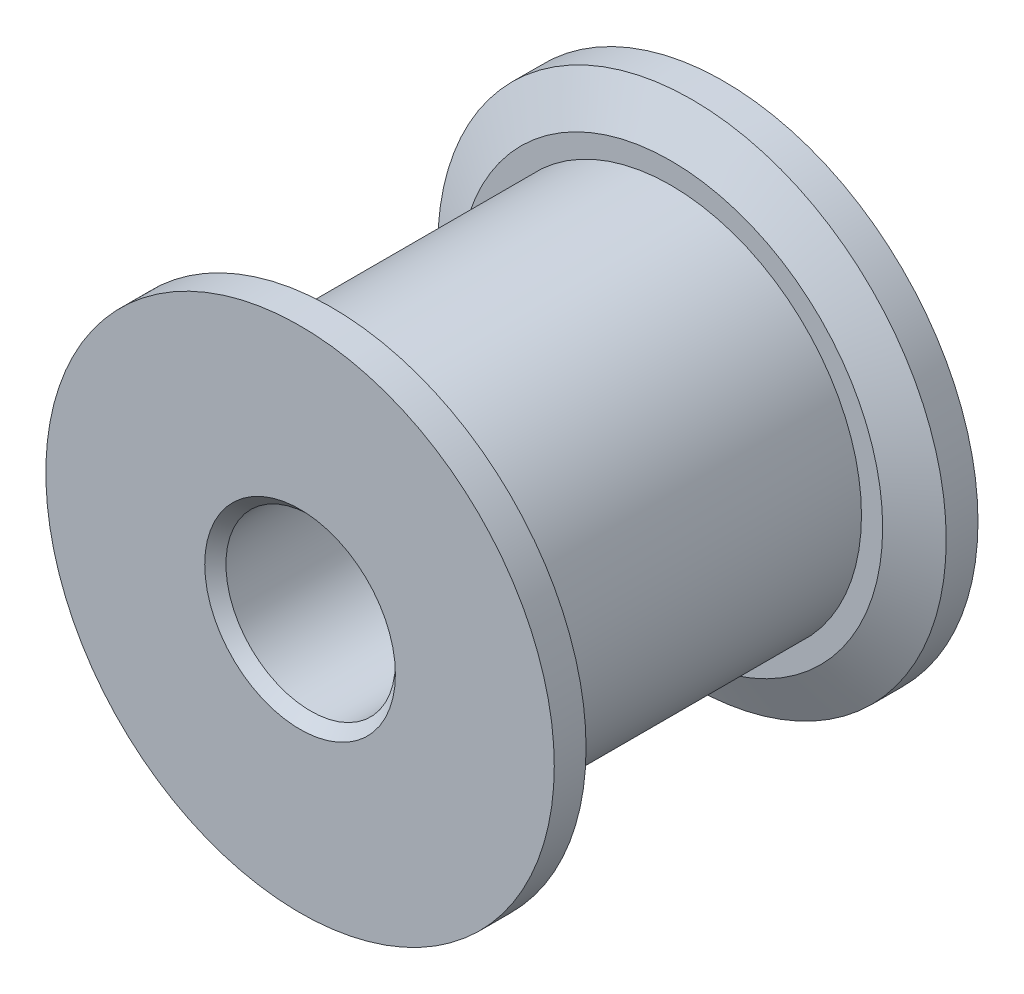
SolidWorks part; units mm, degrees
ref_plane "前视基准面" through (0, 0, 0) normal (0, 0, 1) x (1, 0, 0)
ref_plane "上视基准面" through (0, 0, 0) normal (0, 1, 0) x (1, 0, 0)
ref_plane "右视基准面" through (0, 0, 0) normal (1, 0, 0) x (0, 0, -1)
sketch "Sketch1" plane through (0, 0, 0) normal (0, 0, 1) x (1, 0, 0)
  circle A0 centre (0, 0) radius 18
  dimension "D1" = 36
extrude "Extrude1" add sketch "Sketch1" along normal mid plane 30
sketch "Sketch2" plane through (0, 0, 15) normal (0, 0, 1) x (1, 0, 0)
  circle A0 centre (0, 0) radius 24
  dimension "D1" = 48
extrude "Extrude2" add sketch "Sketch2" along normal blind 5
chamfer "Chamfer2" distance 4 distance2 2 1 edges at (24, 0, 15)
mirror "Mirror2" about plane through (0, 0, 0) normal (0, 0, 1) of "Chamfer2", "Extrude2"
sketch "Sketch3" plane through (0, 0, 0) normal (0, 0, 1) x (1, 0, 0)
  circle A0 centre (0, 0) radius 8
  dimension "D1" = 16
extrude "Extrude3" cut sketch "Sketch3" against normal through all both and the other way through all
chamfer "Chamfer3" distance 1 angle 45 2 edges at (8, 0, 20) (8, 0, -20)
